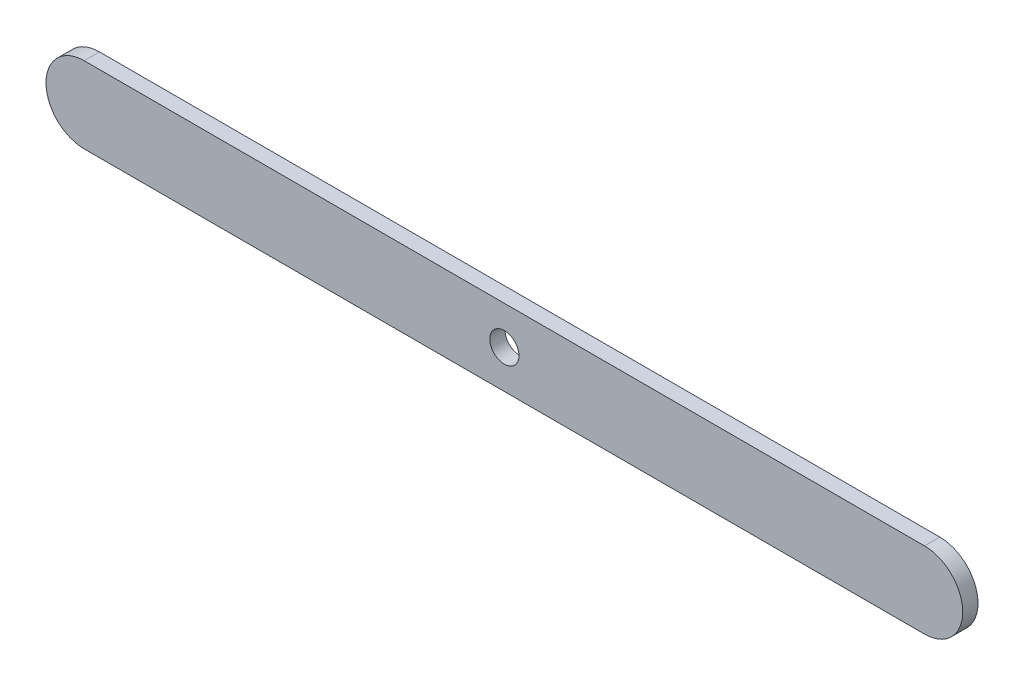
SolidWorks part; units mm, degrees
ref_plane "Front Plane" through (0, 0, 0) normal (0, 0, 1) x (1, 0, 0)
ref_plane "Top Plane" through (0, 0, 0) normal (0, 1, 0) x (1, 0, 0)
ref_plane "Right Plane" through (0, 0, 0) normal (1, 0, 0) x (0, 0, -1)
sketch "Sketch1" plane through (0, 0, 0) normal (0, 0, 1) x (1, 0, 0)
  line L0 (0, 0) -> (139.7, 0) construction
  line L1 (0, 6.35) -> (139.7, 6.35)
  line L2 (0, -6.35) -> (139.7, -6.35)
  arc A0 (0, 6.35) -> (0, -6.35) centre (0, 0) ccw
  arc A1 (139.7, -6.35) -> (139.7, 6.35) centre (139.7, 0) ccw
  circle A2 centre (69.85, 0) radius 2.4257
  point P3 (69.85, 0)
  dimension "D1" = 4.8514
  dimension "D2" = 6.35
  dimension "D3" = 139.7
extrude "Boss-Extrude1" add sketch "Sketch1" along normal blind 2.54
